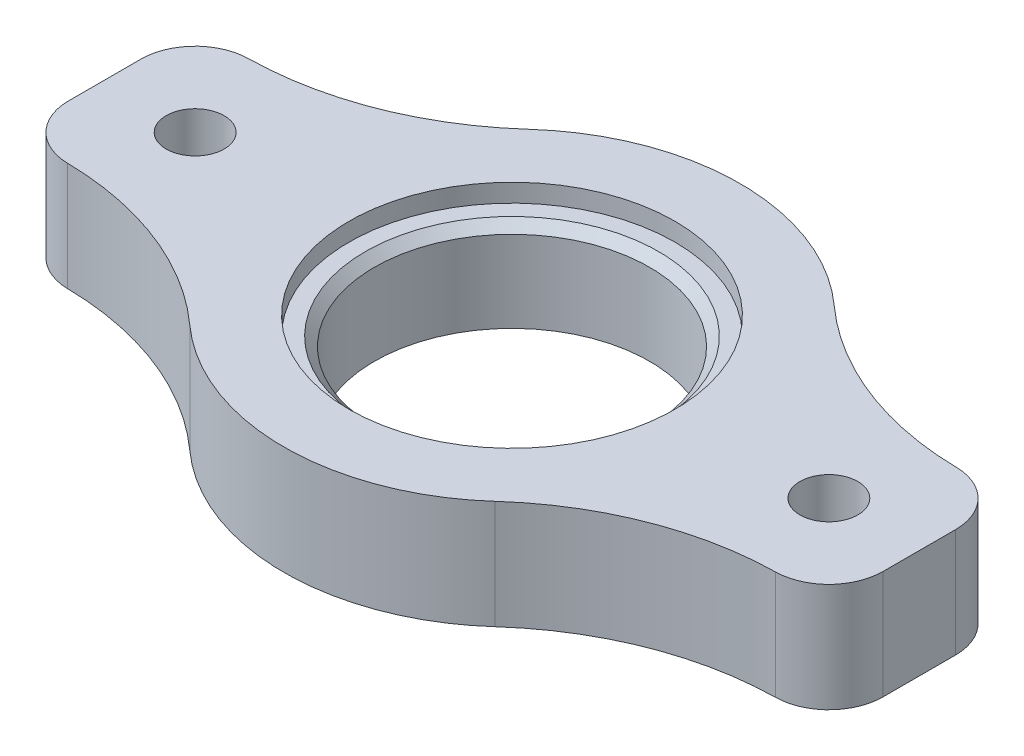
SolidWorks part; units mm, degrees
ref_plane "Front Plane" through (0, 0, 0) normal (0, 0, 1) x (1, 0, 0)
ref_plane "Top Plane" through (0, 0, 0) normal (0, 1, 0) x (1, 0, 0)
ref_plane "Right Plane" through (0, 0, 0) normal (1, 0, 0) x (0, 0, -1)
sketch "Sketch1" plane through (0, 0, 0) normal (0, 1, 0) x (1, 0, 0)
  line L1 (-22.5, 5) -> (22.5, 5)
  line L2 (-22.5, 5) -> (-22.5, -5)
  line L3 (-22.5, -5) -> (22.5, -5)
  line L4 (22.5, 5) -> (22.5, -5)
  circle A0 centre (0, 0) radius 12.6
  circle A1 centre (0, 0) radius 7.6
  circle A2 centre (-17.5, 0) radius 1.6
  circle A3 centre (17.5, 0) radius 1.6
  point P8 (0, 5)
  point P9 (-22.5, 0)
  dimension "D1" = 15.2
  dimension "D2" = 5
  dimension "D5" = 3.2
  dimension "D7" = 5
  dimension "D3" = 10
  dimension "D4" = 45
  dimension "D6" = 5
extrude "Boss-Extrude1" add sketch "Sketch1" along normal blind 6 contours A1 L3 A0 | A0 L1 L2 L3 A2 | A1 L1 A0 L3 | A1 L1 A0 | A1 L3 A0 L1 | A0 L3 L4 L1 A3
fillet "Fillet1" radius 3 4 edges at (22.5, 3, 5) (22.5, 3, -5) (-22.5, 3, 5) (-22.5, 3, -5)
fillet "Fillet2" radius 17 4 edges at (11.5655, 3, -5) (-11.5655, 3, -5) (11.5655, 3, 5) (-11.5655, 3, 5)
sketch "Sketch2" plane through (0, 6, 0) normal (0, 1, 0) x (1, 0, 0)
  circle A0 centre (0, 0) radius 9
  dimension "D1" = 18
extrude "Cut-Extrude1" cut sketch "Sketch2" against normal blind 1
chamfer "Chamfer1" distance 0.5 angle 45 1 edges at (0, 5, 7.6)
sketch "Sketch3" plane through (0, 0, 0) normal (0, -1, 0) x (1, 0, 0)
  circle A0 centre (-17.5, 0) radius 3.25
  circle A1 centre (-17.5, 0) radius 1.6 construction
  circle A2 centre (17.5, 0) radius 3.25
  dimension "D1" = 6.5
extrude "Cut-Extrude2" [suppressed] cut sketch "Sketch3" against normal blind 3
sketch "Sketch4" plane through (0, 6, 0) normal (0, 1, 0) x (1, 0, 0)
  circle A0 centre (-17.5, 0) radius 2.6
  dimension "D1" = 5.2
